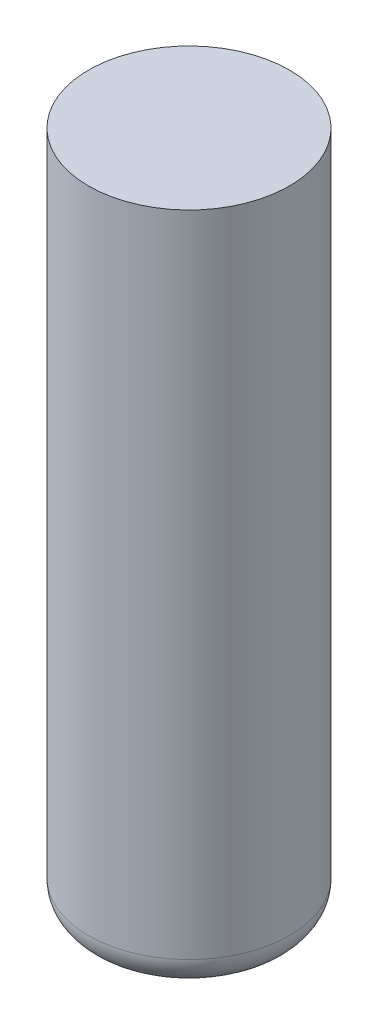
SolidWorks part; units mm, degrees
ref_plane "Front Plane" through (0, 0, 0) normal (0, 0, 1) x (1, 0, 0)
ref_plane "Top Plane" through (0, 0, 0) normal (0, 1, 0) x (1, 0, 0)
ref_plane "Right Plane" through (0, 0, 0) normal (1, 0, 0) x (0, 0, -1)
sketch "Sketch1" plane through (0, 0, 0) normal (0, 1, 0) x (1, 0, 0)
  circle A0 centre (0, 0) radius 32.5
  point P2 (0, 0)
  dimension "D1" = 65
extrude "Boss-Extrude1" add sketch "Sketch1" along normal blind 220
fillet "Fillet1" radius 10 1 edges at (0, 0, 32.5)
